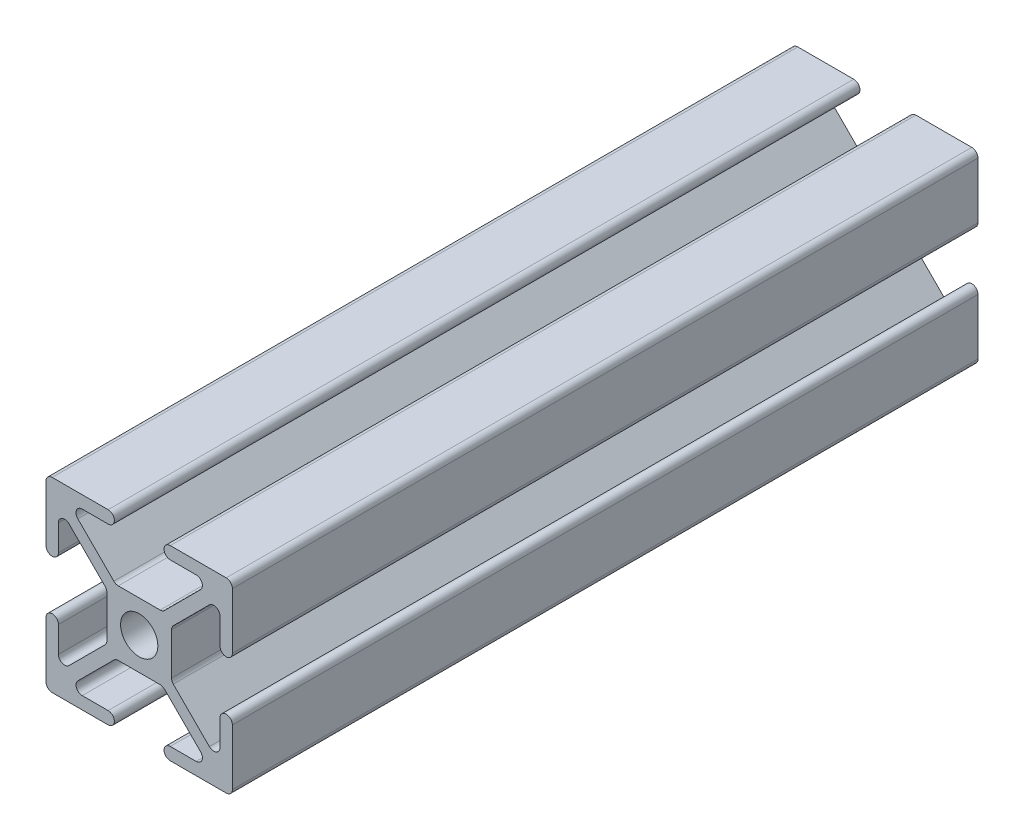
SolidWorks part; units mm, degrees
ref_plane "Alzado" through (0, 0, 0) normal (0, 0, 1) x (1, 0, 0)
ref_plane "Planta" through (0, 0, 0) normal (0, 1, 0) x (1, 0, 0)
ref_plane "Vista lateral" through (0, 0, 0) normal (1, 0, 0) x (0, 0, -1)
sketch "Croquis1" plane through (0, 0, 0) normal (0, 0, 1) x (1, 0, 0)
  line L1 (-14, 15) -> (14, 15)
  line L2 (-15, 14) -> (-15, -14)
  line L3 (-14, -15) -> (14, -15)
  line L4 (15, 14) -> (15, -14)
  line L5 (-15, 15) -> (15, -15) construction
  line L6 (-15, -15) -> (15, 15) construction
  arc A0 (-14, 15) -> (-15, 14) centre (-14, 14) ccw
  arc A1 (14, -15) -> (15, -14) centre (14, -14) ccw
  arc A2 (-14, -15) -> (-15, -14) centre (-14, -14) cw
  arc A3 (15, 14) -> (14, 15) centre (14, 14) ccw
  point P0 (0, 0)
  dimension "D3" = 1
  dimension "D4" = 1
  dimension "D1" = 30
  dimension "D2" = 30
extrude "Saliente-Extruir1" add sketch "Croquis1" against normal blind 120
sketch "Croquis2" plane through (0, 0, 0) normal (0, 0, 1) x (1, 0, 0)
  circle A0 centre (0, 0) radius 3
  dimension "D1" = 6
sketch "Croquis3" plane through (0, 0, 0) normal (0, 0, 1) x (1, 0, 0)
  line L0 (-15, 0) -> (15, 0) construction
  line L1 (4.0787, -5.4929) -> (9.8787, -11.2929)
  line L2 (-11.2929, 9.8787) -> (-5.4929, 4.0787)
  line L3 (-9.8787, 11.2929) -> (-4.0787, 5.4929)
  line L4 (-13, 9.1716) -> (-13, 5)
  line L5 (-15, 14) -> (-15, -14) construction
  line L6 (-5.2, 3.3716) -> (-5.2, -3.3716)
  line L7 (-9.1716, 13) -> (-5, 13)
  line L8 (9.8787, 11.2929) -> (4.0787, 5.4929)
  line L9 (11.2929, 9.8787) -> (5.4929, 4.0787)
  line L10 (-3.3716, 5.2) -> (3.3716, 5.2)
  line L11 (14, 15) -> (-14, 15) construction
  line L12 (13, 9.1716) -> (13, 5)
  line L13 (5.2, 3.3716) -> (5.2, -3.3716)
  line L14 (15, -14) -> (15, 14) construction
  line L15 (-9.1716, -13) -> (-5, -13)
  line L16 (-3.3716, -5.2) -> (3.3716, -5.2)
  line L17 (-14, -15) -> (14, -15) construction
  line L18 (-5.4929, -4.0787) -> (-11.2929, -9.8787)
  line L19 (5.4929, -4.0787) -> (11.2929, -9.8787)
  line L20 (-4.0787, -5.4929) -> (-9.8787, -11.2929)
  line L21 (5, -13) -> (9.1716, -13)
  line L22 (-13, -5) -> (-13, -9.1716)
  line L23 (13, -5) -> (13, -9.1716)
  line L24 (0, 15) -> (0, -5.2) construction
  line L34 (5, 13) -> (9.1716, 13)
  arc A0 (9.8787, 11.2929) -> (9.1716, 13) centre (9.1716, 12) ccw
  arc A1 (-9.8787, 11.2929) -> (-9.1716, 13) centre (-9.1716, 12) cw
  arc A2 (9.8787, 11.2929) -> (9.1716, 13) centre (9.1716, 12) ccw
  arc A3 (13, 9.1716) -> (11.2929, 9.8787) centre (12, 9.1716) ccw
  arc A4 (11.2929, -9.8787) -> (13, -9.1716) centre (12, -9.1716) ccw
  arc A5 (9.1716, -13) -> (9.8787, -11.2929) centre (9.1716, -12) ccw
  arc A6 (-9.1716, -13) -> (-9.8787, -11.2929) centre (-9.1716, -12) cw
  arc A7 (-11.2929, -9.8787) -> (-13, -9.1716) centre (-12, -9.1716) cw
  arc A8 (-13, 9.1716) -> (-11.2929, 9.8787) centre (-12, 9.1716) cw
  arc A9 (-4.0787, -5.4929) -> (-3.3716, -5.2) centre (-3.3716, -6.2) cw
  arc A10 (3.3716, -5.2) -> (4.0787, -5.4929) centre (3.3716, -6.2) cw
  arc A11 (5.4929, -4.0787) -> (5.2, -3.3716) centre (6.2, -3.3716) cw
  arc A12 (5.2, 3.3716) -> (5.4929, 4.0787) centre (6.2, 3.3716) cw
  arc A13 (3.3716, 5.2) -> (4.0787, 5.4929) centre (3.3716, 6.2) ccw
  arc A14 (-3.3716, 5.2) -> (-4.0787, 5.4929) centre (-3.3716, 6.2) cw
  arc A15 (-5.4929, -4.0787) -> (-5.2, -3.3716) centre (-6.2, -3.3716) ccw
  arc A16 (-5.2, 3.3716) -> (-5.4929, 4.0787) centre (-6.2, 3.3716) ccw
  circle A17 centre (-14, -5) radius 1
  circle A18 centre (-14, 5) radius 1
  circle A19 centre (-5, -14) radius 1
  circle A20 centre (5, -14) radius 1
  circle A21 centre (14, 5) radius 1
  circle A22 centre (14, -5) radius 1
  circle A23 centre (-5, 14) radius 1
  circle A24 centre (5, 14) radius 1
  point P20 (-11.5858, -13)
  point P30 (-13, -11.5858)
  point P43 (-3.7858, -5.2)
  point P50 (3.7858, -5.2)
  point P53 (5.2, -3.7858)
  point P62 (-5.2, -3.7858)
  line M2 (-15, 14) -> (-15, -14)
  line M4 (-14, -15) -> (14, -15)
  line M6 (15, -14) -> (15, 14)
  line M8 (14, 15) -> (-14, 15)
  dimension "D6" = 9.8
  dimension "D7" = 2
  dimension "D12" = 2
  dimension "D19" = 1
  dimension "D2" = 1
  dimension "D3" = 1
  dimension "D4" = 1
  dimension "D16" = 1
  dimension "D5" = 2
  dimension "D8" = 9.8
  dimension "D9" = 2
  dimension "D10" = 9.8
  dimension "D11" = 9.8
  dimension "D15" = 1
  dimension "D20" = 1
  dimension "D23" = 1
  dimension "D24" = 1
  dimension "D27" = 1
  dimension "D28" = 1
extrude "Cortar-Extruir1" cut sketch "Croquis2" against normal through all
extrude "Cortar-Extruir3" cut sketch "Croquis3" against normal through all contours A18 A17 L22 A7 L18 A15 L6 A16 L2 A8 L4 M2 | A24 A23 L7 A1 L3 A14 L10 A13 L8 A0 L34 M8 | A20 L21 A5 L1 A10 L16 A9 L20 A6 L15 A19 M4 | A22 A21 L12 A3 L9 A12 L13 A11 L19 A4 L23 M6
